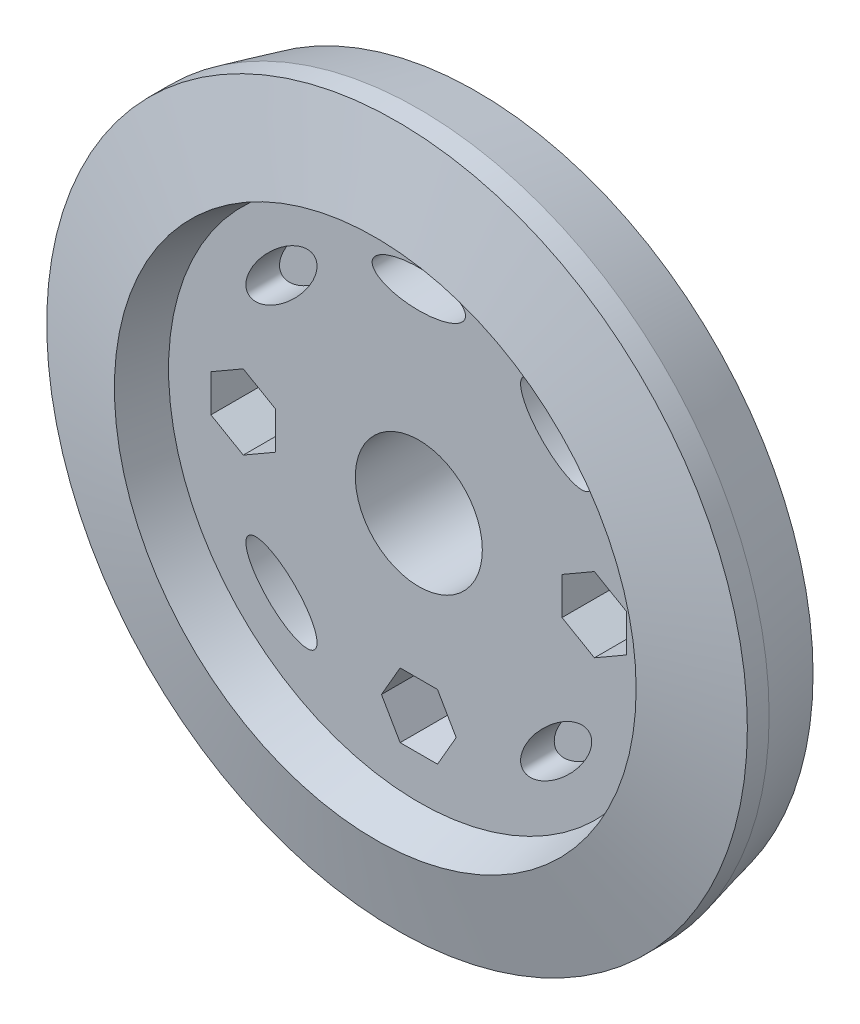
SolidWorks part; units mm, degrees
ref_plane "Front Plane" through (0, 0, 0) normal (0, 0, 1) x (1, 0, 0)
ref_plane "Top Plane" through (0, 0, 0) normal (0, 1, 0) x (1, 0, 0)
ref_plane "Right Plane" through (0, 0, 0) normal (1, 0, 0) x (0, 0, -1)
sketch "Sketch1" plane through (0, 0, 0) normal (1, 0, 0) x (0, 0, -1)
  line L0 (0, 0) -> (2741.9379, 0) construction
  line L1 (-394.8668, 431.8) -> (394.8668, 431.8)
  line L2 (394.8668, 431.8) -> (394.8668, 889)
  line L3 (394.8668, 889) -> (0, 889)
  line L4 (0, 889) -> (0, 2286)
  line L5 (0, 2286) -> (-394.8668, 2382.1309)
  line L6 (-394.8668, 2382.1309) -> (-542.9419, 2382.1309)
  line L7 (-542.9419, 2382.1309) -> (-691.017, 1773.8981)
  line L8 (-691.017, 1773.8981) -> (-394.8668, 1701.8)
  line L9 (-394.8668, 1701.8) -> (-394.8668, 431.8)
  point P14 (-542.9419, 1737.8491)
  point P15 (0, 431.8)
  dimension "D1" = 1397
  dimension "D2" = 406.4
  dimension "D3" = 457.2
  dimension "D4" = 2286
  dimension "D5" = 1701.8
  dimension "D6" = 304.8
revolve "Revolve1" add sketch "Sketch1" angle 360 about L0
sketch "Sketch2" plane through (0, 0, 394.8668) normal (0, 0, 1) x (1, 0, 0)
  ellipse E0 centre (0, 1320.8) end of major axis (-317.5, 1320.8) minor radius 127
  ellipse E1 centre (933.9466, 933.9466) end of major axis (709.4402, 1158.453) minor radius 127
  ellipse E2 centre (1320.8, 0) end of major axis (1320.8, -317.5) minor radius 127 [skipped]
  ellipse E3 centre (933.9466, -933.9466) end of major axis (709.4402, -1158.453) minor radius 127
  ellipse E4 centre (0, -1320.8) end of major axis (-317.5, -1320.8) minor radius 127 [skipped]
  ellipse E5 centre (-933.9466, -933.9466) end of major axis (-1158.453, -709.4402) minor radius 127
  ellipse E6 centre (-1320.8, 0) end of major axis (-1320.8, 317.5) minor radius 127 [skipped]
  ellipse E7 centre (-933.9466, 933.9466) end of major axis (-709.4402, 1158.453) minor radius 127
  point P1 (0, 0)
  point P7 (0, 0)
  point P60 (0, 0)
  dimension "D1" = 635
  dimension "D2" = 254
  dimension "D3" = 1320.8
  dimension "D6" = 8
extrude "Cut-Extrude2" cut sketch "Sketch2" against normal blind 228.6
sketch "Sketch3" plane through (0, 0, 394.8668) normal (0, 0, 1) x (1, 0, 0)
  line L0 (-664.539, -1023.7492) -> (-598.7989, -778.404) [skipped]
  line L1 (254, -1193.8) -> (127, -973.8295)
  line L2 (127, -973.8295) -> (-127, -973.8295)
  line L3 (-127, -973.8295) -> (-254, -1193.8)
  line L4 (-254, -1193.8) -> (-127, -1413.7705)
  line L5 (-127, -1413.7705) -> (127, -1413.7705)
  line L6 (127, -1413.7705) -> (254, -1193.8)
  line L7 (-598.7989, -778.404) -> (-778.404, -598.7989) [skipped]
  line L8 (-778.404, -598.7989) -> (-1023.7492, -664.539) [skipped]
  line L9 (-1023.7492, -664.539) -> (-1089.4892, -909.8841) [skipped]
  line L10 (-1089.4892, -909.8841) -> (-909.8841, -1089.4892) [skipped]
  line L11 (-909.8841, -1089.4892) -> (-664.539, -1023.7492) [skipped]
  line L12 (-1193.8, -254) -> (-973.8295, -127)
  line L13 (-973.8295, -127) -> (-973.8295, 127)
  line L14 (-973.8295, 127) -> (-1193.8, 254)
  line L15 (-1193.8, 254) -> (-1413.7705, 127)
  line L16 (-1413.7705, 127) -> (-1413.7705, -127)
  line L17 (-1413.7705, -127) -> (-1193.8, -254)
  line L18 (-1023.7492, 664.539) -> (-778.404, 598.7989) [skipped]
  line L19 (-778.404, 598.7989) -> (-598.7989, 778.404) [skipped]
  line L20 (-598.7989, 778.404) -> (-664.539, 1023.7492) [skipped]
  line L21 (-664.539, 1023.7492) -> (-909.8841, 1089.4892) [skipped]
  line L22 (-909.8841, 1089.4892) -> (-1089.4892, 909.8841) [skipped]
  line L23 (-1089.4892, 909.8841) -> (-1023.7492, 664.539) [skipped]
  line L24 (-254, 1193.8) -> (-127, 973.8295) [skipped]
  line L25 (-127, 973.8295) -> (127, 973.8295) [skipped]
  line L26 (127, 973.8295) -> (254, 1193.8) [skipped]
  line L27 (254, 1193.8) -> (127, 1413.7705) [skipped]
  line L28 (127, 1413.7705) -> (-127, 1413.7705) [skipped]
  line L29 (-127, 1413.7705) -> (-254, 1193.8) [skipped]
  line L30 (664.539, 1023.7492) -> (598.7989, 778.404) [skipped]
  line L31 (598.7989, 778.404) -> (778.404, 598.7989) [skipped]
  line L32 (778.404, 598.7989) -> (1023.7492, 664.539) [skipped]
  line L33 (1023.7492, 664.539) -> (1089.4892, 909.8841) [skipped]
  line L34 (1089.4892, 909.8841) -> (909.8841, 1089.4892) [skipped]
  line L35 (909.8841, 1089.4892) -> (664.539, 1023.7492) [skipped]
  line L36 (1193.8, 254) -> (973.8295, 127)
  line L37 (973.8295, 127) -> (973.8295, -127)
  line L38 (973.8295, -127) -> (1193.8, -254)
  line L39 (1193.8, -254) -> (1413.7705, -127)
  line L40 (1413.7705, -127) -> (1413.7705, 127)
  line L41 (1413.7705, 127) -> (1193.8, 254)
  line L42 (1023.7492, -664.539) -> (778.404, -598.7989) [skipped]
  line L43 (778.404, -598.7989) -> (598.7989, -778.404) [skipped]
  line L44 (598.7989, -778.404) -> (664.539, -1023.7492) [skipped]
  line L45 (664.539, -1023.7492) -> (909.8841, -1089.4892) [skipped]
  line L46 (909.8841, -1089.4892) -> (1089.4892, -909.8841) [skipped]
  line L47 (1089.4892, -909.8841) -> (1023.7492, -664.539) [skipped]
  circle A0 centre (0, -1193.8) radius 219.9705 construction
  point P54 (0, 0)
  dimension "D1" = 254
  dimension "D2" = 1193.8
  dimension "D3" = 8
extrude "Cut-Extrude3" cut sketch "Sketch3" against normal through all
